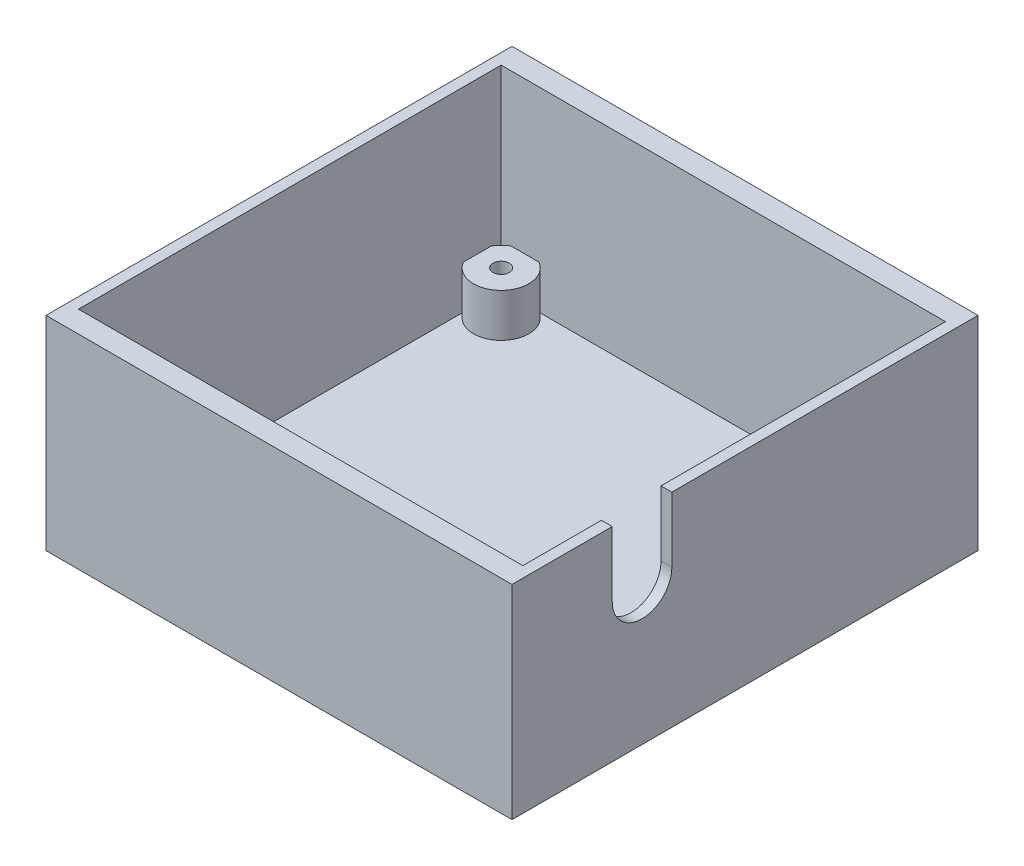
SolidWorks part; units mm, degrees
ref_plane "Front Plane" through (0, 0, 0) normal (0, 0, 1) x (1, 0, 0)
ref_plane "Top Plane" through (0, 0, 0) normal (0, 1, 0) x (1, 0, 0)
ref_plane "Right Plane" through (0, 0, 0) normal (1, 0, 0) x (0, 0, -1)
sketch "Sketch1" plane through (0, 0, 0) normal (0, 1, 0) x (1, 0, 0)
  line L1 (-20.5, 19.5) -> (20.5, 19.5)
  line L2 (-20.5, 19.5) -> (-20.5, -19.5)
  line L3 (-20.5, -19.5) -> (20.5, -19.5)
  line L4 (20.5, 19.5) -> (20.5, -19.5)
  line L5 (-20.5, 19.5) -> (20.5, -19.5) construction
  line L6 (-20.5, -19.5) -> (20.5, 19.5) construction
  line L7 (-21.5, 21.5) -> (21.5, 21.5)
  line L8 (-21.5, 21.5) -> (-21.5, -21.5)
  line L9 (-21.5, -21.5) -> (21.5, -21.5)
  line L10 (21.5, 21.5) -> (21.5, -21.5)
  line L11 (-21.5, 21.5) -> (21.5, -21.5) construction
  line L12 (-21.5, -21.5) -> (21.5, 21.5) construction
  point P0 (0, 0)
  point P6 (0, 0)
  dimension "D1" = 39
  dimension "D2" = 41
  dimension "D3" = 2
  dimension "D4" = 1
extrude "Boss-Extrude1" add sketch "Sketch1" along normal blind 18
sketch "Sketch2" plane through (0, 0, 0) normal (0, -1, 0) x (1, 0, 0)
  line L1 (21.5, -21.5) -> (-21.5, -21.5)
  line L2 (21.5, -21.5) -> (21.5, 21.5)
  line L3 (21.5, 21.5) -> (-21.5, 21.5)
  line L4 (-21.5, -21.5) -> (-21.5, 21.5)
  line L5 (21.5, -21.5) -> (-21.5, 21.5) construction
  line L6 (21.5, 21.5) -> (-21.5, -21.5) construction
  point P0 (0, 0)
extrude "Boss-Extrude2" add sketch "Sketch2" along normal blind 0.8
sketch "Sketch3" plane through (0, 0, 0) normal (0, 1, 0) x (1, 0, 0)
  line L0 (20.5, 19.5) -> (-20.5, 19.5) construction
  line L1 (-20.5, 19.5) -> (-20.5, -19.5) construction
  line L2 (20.5, -19.5) -> (20.5, 19.5) construction
  line L3 (-20.5, -19.5) -> (20.5, -19.5) construction
  line L4 (-20.5, -19.5) -> (20.5, -19.5) construction
  line L5 (-20.5, 19.5) -> (-20.5, -19.5) construction
  circle A0 centre (18.3, 17.3) radius 0.75
  circle A1 centre (-18.3, 17.3) radius 0.75
  circle A2 centre (-18.3, -17.3) radius 0.75
  circle A3 centre (18.3, -17.3) radius 0.75
  dimension "D1" = 1.5
  dimension "D2" = 1.5
  dimension "D3" = 1.5
  dimension "D4" = 1.5
  dimension "D5" = 2.2
  dimension "D6" = 2.2
  dimension "D7" = 2.2
  dimension "D8" = 2.2
  dimension "D9" = 2.2
  dimension "D10" = 2.2
  dimension "D11" = 2.2
  dimension "D12" = 2.2
extrude "Cut-Extrude1" cut sketch "Sketch3" against normal blind 10.8
sketch "Sketch4" plane through (0, 0, 0) normal (0, 1, 0) x (1, 0, 0)
  circle A0 centre (-18.3, 17.3) radius 0.75
  circle A1 centre (-18.3, 17.3) radius 2.55
  circle A2 centre (18.3, 17.3) radius 0.75
  circle A3 centre (18.3, 17.3) radius 2.55
  circle A4 centre (18.3, -17.3) radius 0.75
  circle A5 centre (18.3, -17.3) radius 2.55
  circle A6 centre (-18.3, -17.3) radius 0.75
  circle A7 centre (-18.3, -17.3) radius 2.55
  dimension "D1" = 1.8
  dimension "D2" = 1.8
  dimension "D3" = 1.8
  dimension "D4" = 1.8
extrude "Boss-Extrude3" add sketch "Sketch4" along normal blind 4
sketch "Sketch5" plane through (21.5, 0, 0) normal (1, 0, 0) x (0, 0, -1)
  line L0 (-21.5, 18) -> (-21.5, -0.8) construction
  line L1 (-21.5, 18) -> (21.5, 18) construction
  line L4 (-12.25, 12) -> (-12.25, 18)
  line L5 (-12.25, 18) -> (-6.75, 18)
  line L6 (-6.75, 12) -> (-6.75, 18)
  arc A0 (-12.25, 12) -> (-6.75, 12) centre (-9.5, 12) ccw
  dimension "D1" = 5.5
  dimension "D2" = 12
  dimension "D3" = 6
extrude "Cut-Extrude2" cut sketch "Sketch5" against normal blind 4
